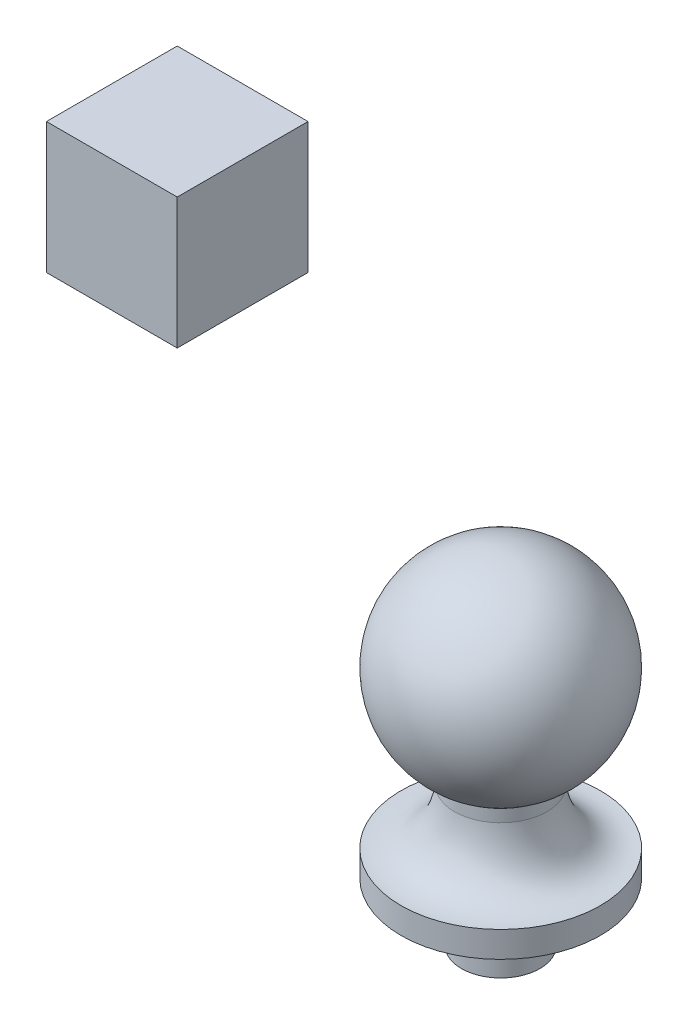
SolidWorks part; units mm, degrees
ref_plane "Front Plane" through (0, 0, 0) normal (0, 0, 1) x (1, 0, 0)
ref_plane "Top Plane" through (0, 0, 0) normal (0, 1, 0) x (1, 0, 0)
ref_plane "Right Plane" through (0, 0, 0) normal (1, 0, 0) x (0, 0, -1)
sketch "Sketch1" plane through (0, 0, 0) normal (1, 0, 0) x (0, 0, -1)
  line L0 (0, 38.956) -> (0, -39.2057) construction
  line L1 (0, 25.4) -> (0, -25.4)
  line L2 (-11.7541, -22.5167) -> (-11.7541, -25.954)
  line L3 (-25.4, -39.8463) -> (-25.4, -46.4531)
  line L4 (-25.4, -46.4531) -> (0, -46.4531)
  line L5 (0, -46.4531) -> (0, -25.4)
  line L6 (-10, -46.4531) -> (-10, -61.4531)
  line L7 (-10, -61.4531) -> (0, -61.4531)
  line L8 (0, -61.4531) -> (0, -46.4531)
  arc A0 (0, 25.4) -> (0, -25.4) centre (0, 0) ccw
  spline S0 degree 2 poles (-11.7541, -25.954) (-13.6251, -40.6638) (-25.4, -39.8463) knots 0 0 0 1 1 1
  dimension "D1" = 50.8
  dimension "D2" = 25.4
  dimension "D3" = 10
  dimension "D4" = 15
revolve "Revolve2" add sketch "Sketch1" angle 360 about L0
ref_plane "Right P" through (0, 0, 0) normal (1, 0, 0) x (0, 0, -1)
ref_plane "Front P" through (0, 0, 0) normal (0, 0, 1) x (1, 0, 0)
scale "Scale1" scale about centroid uniform scaling yes scale factor 0.3
sketch "Sketch5" plane through (0, 0, 0) normal (0, 0, 1) x (1, 0, 0)
  line L1 (-29.7311, 15.3258) -> (-19.7311, 15.3258)
  line L2 (-29.7311, 15.3258) -> (-29.7311, 5.3258)
  line L3 (-29.7311, 5.3258) -> (-19.7311, 5.3258)
  line L4 (-19.7311, 15.3258) -> (-19.7311, 5.3258)
  dimension "D1" = 10
  dimension "D2" = 10
extrude "Boss-Extrude1" add sketch "Sketch5" along normal mid plane 10 separate body
